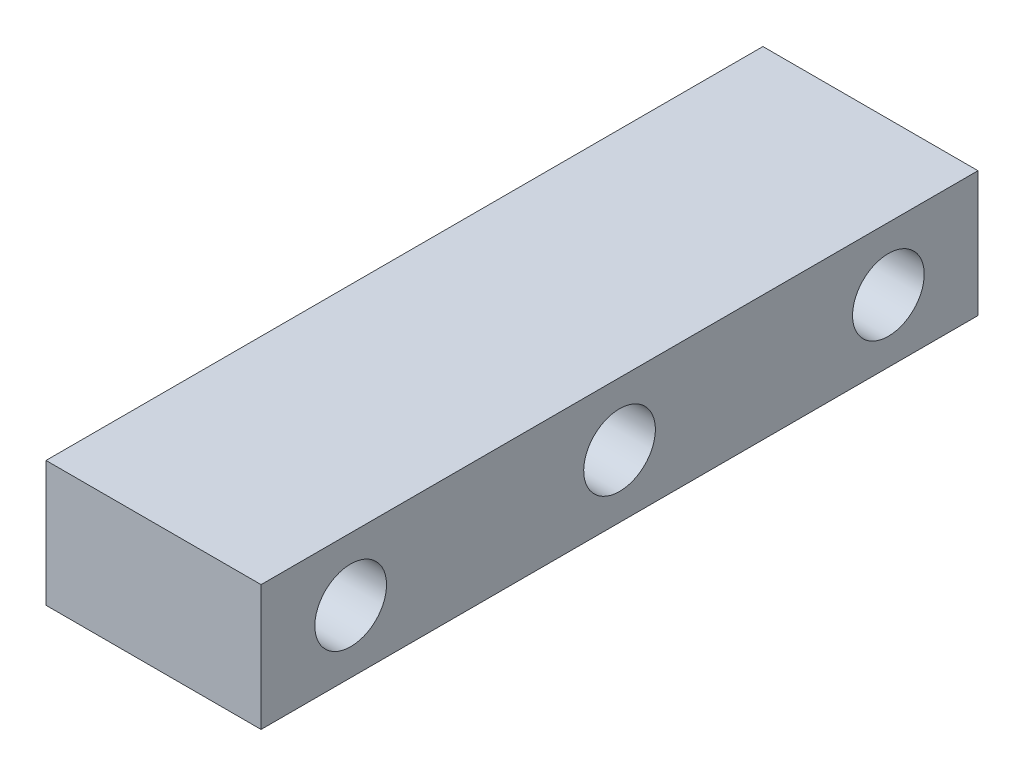
SolidWorks part; units mm, degrees
ref_plane "前视基准面" through (0, 0, 0) normal (0, 0, 1) x (1, 0, 0)
ref_plane "上视基准面" through (0, 0, 0) normal (0, 1, 0) x (1, 0, 0)
ref_plane "右视基准面" through (0, 0, 0) normal (1, 0, 0) x (0, 0, -1)
sketch "草图1" plane through (0, 0, 0) normal (0, 0, 1) x (1, 0, 0)
  line L1 (0, 0) -> (24, 0)
  line L2 (0, 0) -> (0, -14)
  line L3 (0, -14) -> (24, -14)
  line L4 (24, 0) -> (24, -14)
  dimension "D1" = 14
  dimension "D2" = 24
extrude "拉伸1" add sketch "草图1" along normal blind 90
sketch "草图2" plane through (0, 0, 0) normal (-1, 0, 0) x (0, 0, 1)
  line L0 (0, 0) -> (0, -14) construction
  circle A0 centre (15, -7) radius 4
  circle A1 centre (45, -7) radius 4
  circle A2 centre (75, -7) radius 4
  dimension "D1" = 8
  dimension "D2" = 15
extrude "切除-拉伸1" cut sketch "草图2" against normal blind 90
sketch "草图3" plane through (24, 0, 0) normal (1, 0, 0) x (0, 0, -1)
  line L0 (-90, -14) -> (0, -14) construction
  line L1 (-90, 0) -> (-85, 0)
  line L2 (-90, 0) -> (-90, -14)
  line L3 (-90, -14) -> (-85, -14)
  line L4 (-85, 0) -> (-85, -14)
  line L6 (0, 0) -> (-5, 0)
  line L7 (0, 0) -> (0, -14)
  line L8 (0, -14) -> (-5, -14)
  line L9 (-5, 0) -> (-5, -14)
  dimension "D1" = 5
  dimension "D2" = 5
extrude "切除-拉伸2" cut sketch "草图3" against normal through all
